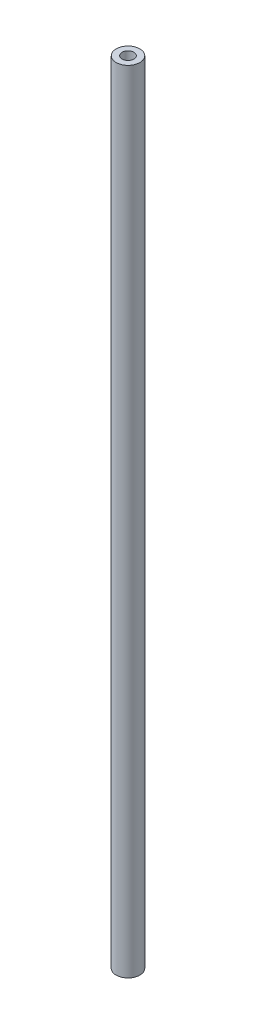
SolidWorks part; units mm, degrees
ref_plane "前视基准面" through (0, 0, 0) normal (0, 0, 1) x (1, 0, 0)
ref_plane "上视基准面" through (0, 0, 0) normal (0, 1, 0) x (1, 0, 0)
ref_plane "右视基准面" through (0, 0, 0) normal (1, 0, 0) x (0, 0, -1)
sketch "草图2" plane through (0, 0, 0) normal (0, 1, 0) x (1, 0, 0)
  circle A0 centre (0, 0) radius 3
  circle A1 centre (0, 0) radius 1.5
extrude "凸台-拉伸1" add sketch "草图2" along normal blind 200
